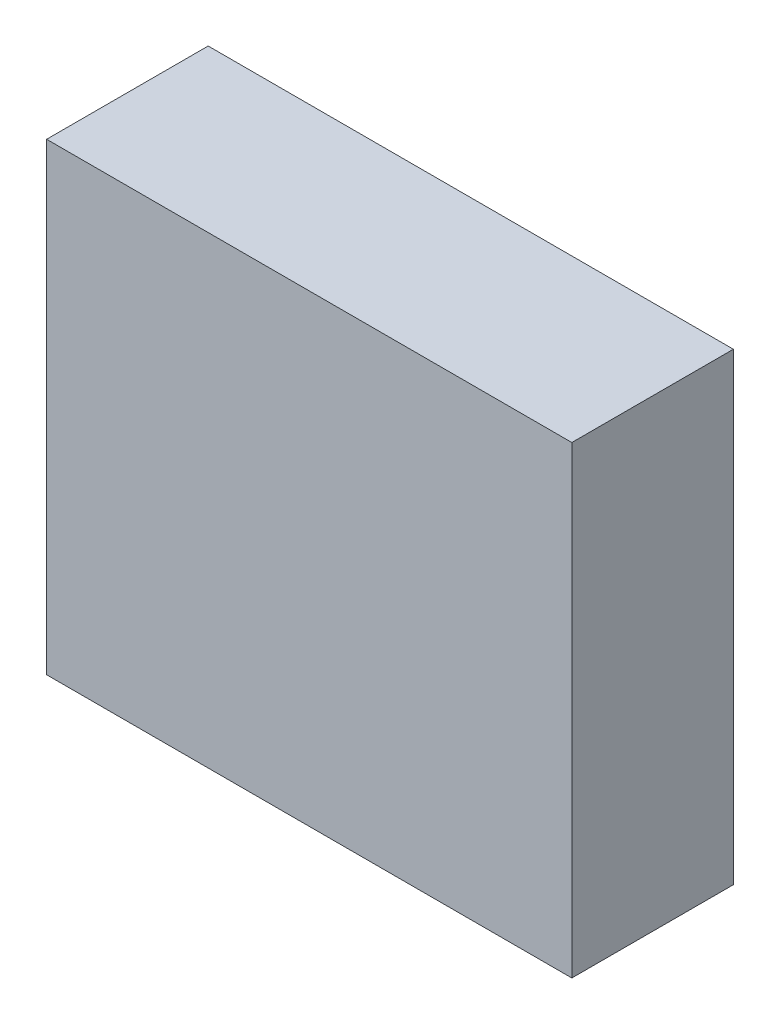
SolidWorks part; units mm, degrees
ref_plane "Front Plane" through (0, 0, 0) normal (0, 0, 1) x (1, 0, 0)
ref_plane "Top Plane" through (0, 0, 0) normal (0, 1, 0) x (1, 0, 0)
ref_plane "Right Plane" through (0, 0, 0) normal (1, 0, 0) x (0, 0, -1)
sketch "Sketch1" plane through (0, 0, 0) normal (0, 0, 1) x (1, 0, 0)
  line L0 (-1.6256, 1.3208) -> (1.6256, 1.3208)
  line L1 (1.6256, 1.3208) -> (1.6256, -1.55)
  line L2 (1.6256, -1.55) -> (-1.6256, -1.55)
  line L3 (-1.6256, -1.55) -> (-1.6256, 1.3208)
extrude "Component_Outline" add sketch "Sketch1" along normal blind 1 separate body
sketch3d "3DSketch1"
  line L0 (0, 0, 0) -> (1, 0, 0)
  line L1 (0, 0, 0) -> (0, 1, 0)
  line L2 (0, 0, 0) -> (0, 0, 1)
  point P0 (0, 0, 0)
